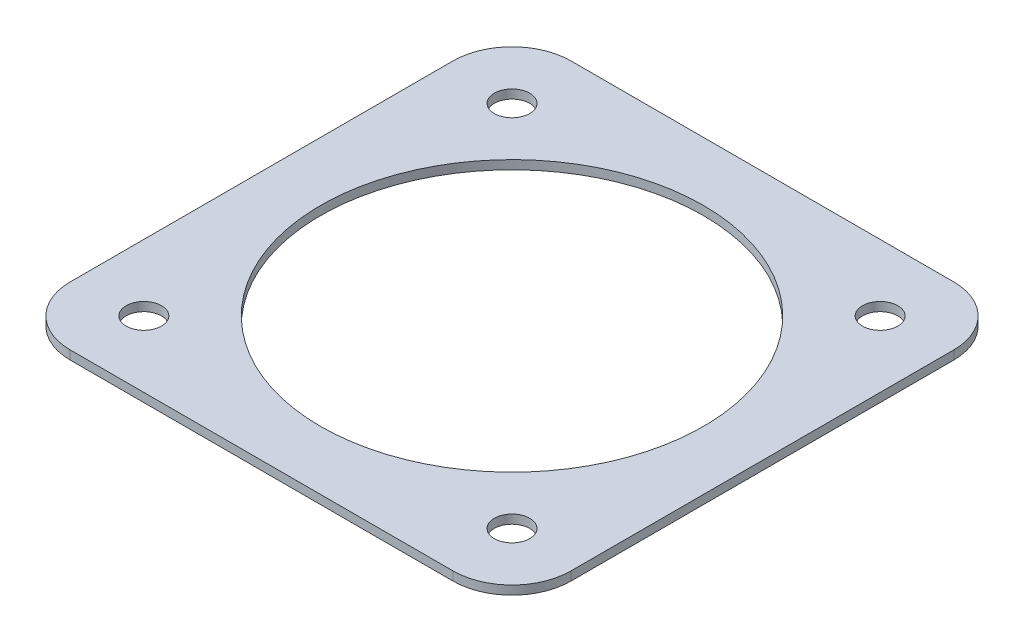
SolidWorks part; units mm, degrees
material "Гофрированная бумага"
ref_plane "Спереди" through (0, 0, 0) normal (0, 0, 1) x (1, 0, 0)
ref_plane "Сверху" through (0, 0, 0) normal (0, 1, 0) x (1, 0, 0)
ref_plane "Справа" through (0, 0, 0) normal (1, 0, 0) x (0, 0, -1)
sketch "Эскиз1" plane through (0, 0, 0) normal (0, 1, 0) x (1, 0, 0)
  line L1 (65, -85) -> (-65, -85)
  line L2 (85, -65) -> (85, 65)
  line L3 (65, 85) -> (-65, 85)
  line L4 (-85, -65) -> (-85, 65)
  line L5 (85, -85) -> (-85, 85) construction
  line L6 (85, 85) -> (-85, -85) construction
  arc A0 (-85, -65) -> (-65, -85) centre (-65, -65) ccw
  arc A1 (65, -85) -> (85, -65) centre (65, -65) ccw
  arc A2 (85, 65) -> (65, 85) centre (65, 65) ccw
  arc A3 (-65, 85) -> (-85, 65) centre (-65, 65) ccw
  circle A4 centre (-62.5, -62.5) radius 6
  circle A5 centre (-62.5, 62.5) radius 6
  circle A6 centre (62.5, 62.5) radius 6
  circle A7 centre (62.5, -62.5) radius 6
  circle A8 centre (0, 0) radius 65
  point P0 (0, 0)
  point P29 (0, 0)
  dimension "D2" = 20
  dimension "D3" = 12
  dimension "D6" = 130
  dimension "D1" = 170
  dimension "D4" = 62.5
  dimension "D5" = 4
extrude "Бобышка-Вытянуть1" add sketch "Эскиз1" along normal blind 3
